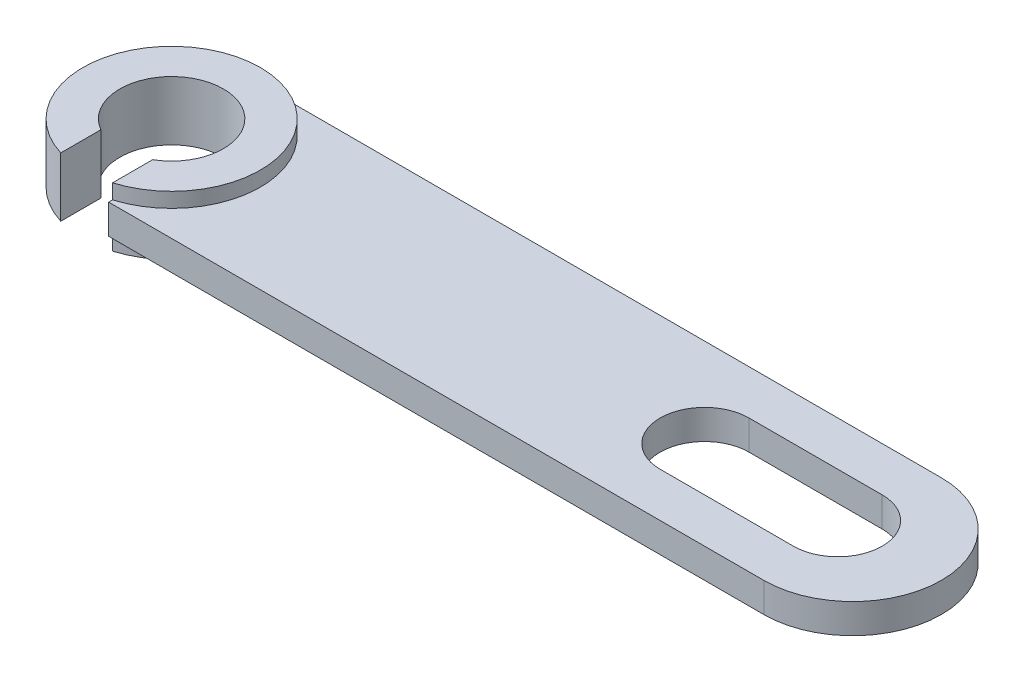
SolidWorks part; units mm, degrees
material "ABS PC"
ref_plane "Piano frontale" through (0, 0, 0) normal (0, 0, 1) x (1, 0, 0)
ref_plane "Piano superiore" through (0, 0, 0) normal (0, 1, 0) x (1, 0, 0)
ref_plane "Piano destro" through (0, 0, 0) normal (1, 0, 0) x (0, 0, -1)
sketch "Schizzo1" plane through (0, 0, 0) normal (0, 1, 0) x (1, 0, 0)
  line L0 (-11.5, 0) -> (11.5, 0) construction
  line L1 (-11.5, 3) -> (11.5, 3)
  line L2 (-11.5, -3) -> (11.5, -3)
  line L3 (11, 0) -> (6.5, 0) construction
  line L4 (11, -1.5) -> (6.5, -1.5)
  line L5 (11, 1.5) -> (6.5, 1.5)
  line L6 (-11.5, 0) -> (-11.5, -3) construction
  arc A0 (-11.5, 3) -> (-11.5, -3) centre (-11.5, 0) ccw
  arc A1 (11.5, -3) -> (11.5, 3) centre (11.5, 0) ccw
  arc A2 (11, -1.5) -> (11, 1.5) centre (11, 0) ccw
  arc A3 (6.5, 1.5) -> (6.5, -1.5) centre (6.5, 0) ccw
  circle A4 centre (-11.5, 0) radius 1.75
  point P2 (0, 0)
  point P8 (-14.5, 0)
  point P9 (14.5, 0)
  point P12 (8.75, 0)
  point P19 (12.5, 0)
  dimension "D3" = 1.5
  dimension "D5" = 4.5
  dimension "D6" = 3.5
  dimension "D1" = 29
  dimension "D2" = 6
  dimension "D4" = 2
extrude "Estrusione-Estrusione1" add sketch "Schizzo1" along normal mid plane 1
sketch "Schizzo2" plane through (0, 0, 0) normal (0, 1, 0) x (1, 0, 0)
  line L0 (-11.5, 0) -> (-10.625, -1.5155) construction
  line L2 (-11.5, 0) -> (-12.375, -1.5155) construction
  line L3 (-11.5, 0) -> (-11.5, -3) construction
  line L4 (-10.625, -1.5155) -> (-10.625, -3)
  line L5 (-12.375, -1.5155) -> (-12.375, -2.8696)
  line L6 (-11.5, -3) -> (-13.3746, -3) construction
  line L7 (-11.5, -3) -> (11.5, -3) construction
  line L8 (-11.5, -3) -> (-10.625, -3)
  circle A0 centre (-11.5, 0) radius 1.75 construction
  arc A1 (-12.375, -1.5155) -> (-10.625, -1.5155) centre (-11.5, 0) ccw
  arc A2 (-12.375, -2.8696) -> (-11.5, -3) centre (-11.5, 0) ccw
  arc A3 (-11.5, 3) -> (-11.5, -3) centre (-11.5, 0) ccw construction
  dimension "D1" = 30
  dimension "D2" = 30
extrude "Taglio-Estrusione2" cut sketch "Schizzo2" against normal through all both and the other way through all
sketch "Schizzo4" plane through (0, 0, 0) normal (0, 1, 0) x (1, 0, 0)
  line L0 (-10.625, -3) -> (-10.625, -1.5155) construction
  line L1 (-12.375, -1.5155) -> (-12.375, -2.8696) construction
  line L2 (-10.625, -2.8696) -> (-10.625, -1.5155)
  line L3 (-12.375, -1.5155) -> (-12.375, -2.8696)
  arc A0 (-10.625, -2.8696) -> (-12.375, -2.8696) centre (-11.5, 0) ccw
  arc A1 (-10.625, -1.5155) -> (-12.375, -1.5155) centre (-11.5, 0) ccw construction
  arc A2 (-10.625, -1.5155) -> (-12.375, -1.5155) centre (-11.5, 0) ccw
extrude "Estrusione-Estrusione2" add sketch "Schizzo4" along normal mid plane 2
sketch "Schizzo5" plane through (0, 0, 0) normal (0, 1, 0) x (1, 0, 0)
  line L0 (-11.5, 0) -> (14.5, 0) construction
  arc A0 (11.5, -3) -> (11.5, 3) centre (11.5, 0) ccw construction
